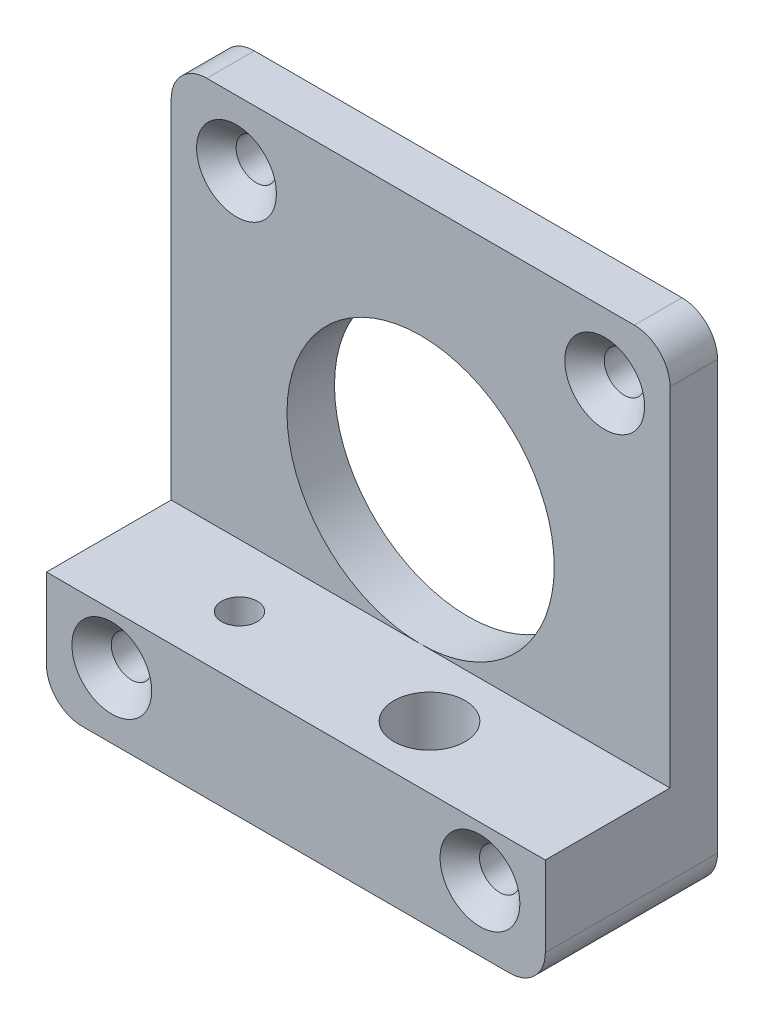
SolidWorks part; units mm, degrees
material "Aleación 6061"
ref_plane "Alzado" through (0, 0, 0) normal (0, 0, 1) x (1, 0, 0)
ref_plane "Planta" through (0, 0, 0) normal (0, 1, 0) x (1, 0, 0)
ref_plane "Vista lateral" through (0, 0, 0) normal (1, 0, 0) x (0, 0, -1)
sketch "Croquis1" plane through (0, 0, 0) normal (0, 0, 1) x (1, 0, 0)
  line L1 (-18, 21) -> (18, 21)
  line L2 (-21, 18) -> (-21, -18)
  line L3 (-18, -21) -> (18, -21)
  line L4 (21, 18) -> (21, -18)
  line L5 (-21, 21) -> (21, -21) construction
  line L6 (-21, -21) -> (21, 21) construction
  line L7 (-15.5, 15.5) -> (15.5, 15.5) construction
  line L8 (-15.5, 15.5) -> (-15.5, -15.5) construction
  line L9 (-15.5, -15.5) -> (15.5, -15.5) construction
  line L10 (15.5, 15.5) -> (15.5, -15.5) construction
  line L11 (-15.5, 15.5) -> (15.5, -15.5) construction
  line L12 (-15.5, -15.5) -> (15.5, 15.5) construction
  circle A0 centre (-15.5, 15.5) radius 1
  circle A1 centre (15.5, 15.5) radius 1
  circle A2 centre (15.5, -15.5) radius 1
  circle A3 centre (-15.5, -15.5) radius 1
  circle A4 centre (0, 0) radius 11.25
  arc A5 (-21, -18) -> (-18, -21) centre (-18, -18) ccw
  arc A6 (18, -21) -> (21, -18) centre (18, -18) ccw
  arc A7 (18, 21) -> (21, 18) centre (18, 18) cw
  arc A8 (-18, 21) -> (-21, 18) centre (-18, 18) ccw
  point P0 (0, 0)
  point P6 (0, 0)
  dimension "D3" = 2
  dimension "D4" = 22.5
  dimension "D5" = 3
  dimension "D1" = 42
  dimension "D2" = 31
extrude "Saliente-Extruir1" add sketch "Croquis1" along normal blind 4
sketch "Croquis2" plane through (0, 0, 4) normal (0, 0, 1) x (1, 0, 0)
  line L0 (-21, 18) -> (-21, -18) construction
  line L1 (-21, -11.25) -> (21, -11.25)
  line L2 (-21, -11.25) -> (-21, -18)
  line L3 (-18, -21) -> (18, -21)
  line L4 (21, -11.25) -> (21, -18)
  line L5 (-18, -21) -> (18, -21) construction
  line L6 (21, -18) -> (21, 18) construction
  circle A0 centre (0, 0) radius 11.25 construction
  arc A1 (18, -21) -> (21, -18) centre (18, -18) ccw
  arc A2 (-21, -18) -> (-18, -21) centre (-18, -18) ccw
  circle A3 centre (15.5, -15.5) radius 1 construction
  circle A4 centre (-15.5, -15.5) radius 1 construction
  circle A5 centre (15.5, -15.5) radius 1
  circle A6 centre (-15.5, -15.5) radius 1
  dimension "D1" = 3
extrude "Saliente-Extruir2" add sketch "Croquis2" along normal blind 10.5
sketch "Croquis3" plane through (0, -11.25, 0) normal (0, 1, 0) x (1, 0, 0)
  line L0 (21, -14.5) -> (21, -4) construction
  line L1 (-21, -14.5) -> (-21, -4) construction
  circle A0 centre (6, -9.25) radius 3
  circle A1 centre (-10, -9.25) radius 1.5
  point P5 (21, -9.25)
  dimension "D1" = 6
  dimension "D3" = 3
  dimension "D2" = 15
  dimension "D4" = 11
extrude "Cortar-Extruir1" cut sketch "Croquis3" against normal up to surface (9.75 mm away) up to face at (0, -21, 7.25)
hole_wizard "Refrentado para tornillo tapón con cabeza plana de clavija de M31" positions "Croquis4" profile "Croquis5" countersink size "M3" standard "Ansi Metric" end condition through all
sketch "Croquis4" plane through (0, 0, 4) normal (0, 0, 1) x (1, 0, 0)
  point P0 (-15.5, 15.5)
  point P3 (15.5, 15.5)
sketch "Croquis5" plane through (-15.5, 15.5, 4) normal (1, 0, 0) x (0, -1, 0)
  line L0 (0, 0) -> (0, 4)
  line L1 (0, 4) -> (1.7, 4)
  line L2 (1.7, 4) -> (1.7, 1.66)
  line L3 (1.7, 1.66) -> (3.36, 0)
  line L5 (3.36, 0) -> (0, 0)
  line L6 (-1.7, 1.66) -> (-3.36, 0) construction
  line L11 (0, -6.35) -> (0, 107.95) construction
  dimension "Diámetro de taladro hasta el siguiente" = 3.4
  dimension "Profundidad de taladro hasta el siguiente" = 4
  dimension "Diámetro de avellanado cercano" = 6.72
  dimension "Ángulo de avellanado cercano" = 90
hole_wizard "Refrentado para tornillo tapón con cabeza plana de clavija de M32" positions "Croquis6" profile "Croquis7" countersink size "M3" standard "Ansi Metric" end condition through all
sketch "Croquis6" plane through (0, 0, 14.5) normal (0, 0, 1) x (1, 0, 0)
  point P0 (-15.5, -15.5)
  point P3 (15.5, -15.5)
sketch "Croquis7" plane through (-15.5, -15.5, 14.5) normal (1, 0, 0) x (0, -1, 0)
  line L0 (0, 0) -> (0, 14.5)
  line L1 (0, 14.5) -> (1.7, 14.5)
  line L2 (1.7, 14.5) -> (1.7, 1.66)
  line L3 (1.7, 1.66) -> (3.36, 0)
  line L5 (3.36, 0) -> (0, 0)
  line L6 (-1.7, 1.66) -> (-3.36, 0) construction
  line L11 (0, -6.35) -> (0, 107.95) construction
  dimension "Diámetro de taladro hasta el siguiente" = 3.4
  dimension "Profundidad de taladro hasta el siguiente" = 14.5
  dimension "Diámetro de avellanado cercano" = 6.72
  dimension "Ángulo de avellanado cercano" = 90
